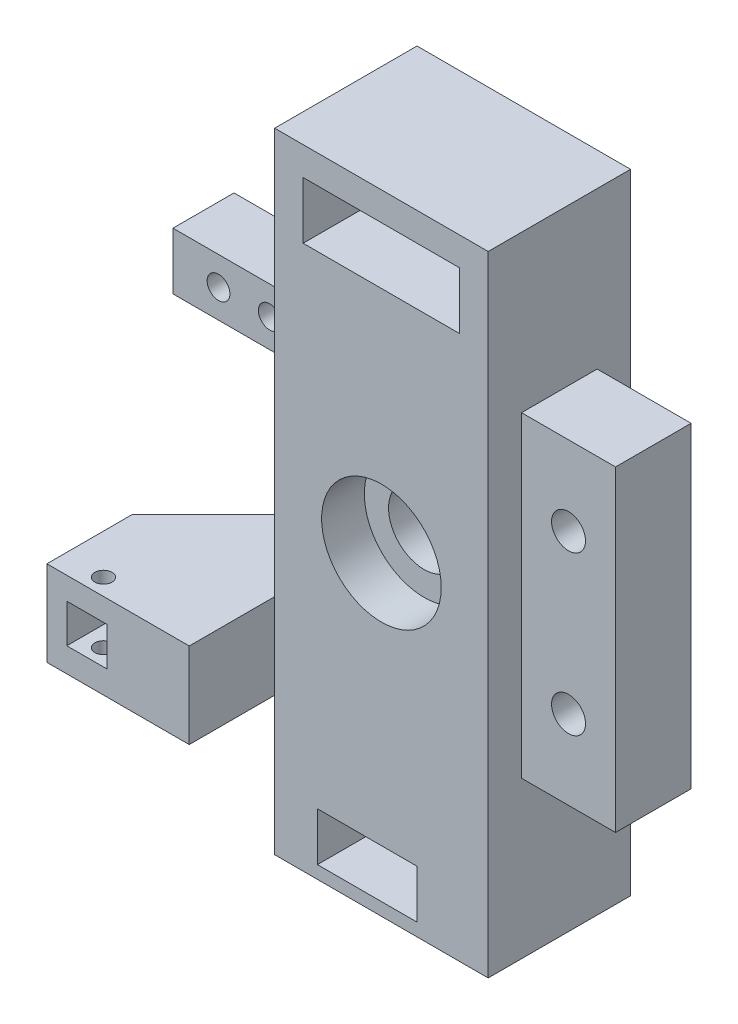
SolidWorks part; units mm, degrees
ref_plane "Front Plane" through (0, 0, 0) normal (0, 0, 1) x (1, 0, 0)
ref_plane "Top Plane" through (0, 0, 0) normal (0, 1, 0) x (1, 0, 0)
ref_plane "Right Plane" through (0, 0, 0) normal (1, 0, 0) x (0, 0, -1)
sketch "Sketch1" plane through (0, 0, 0) normal (0, 1, 0) x (1, 0, 0)
  line L1 (-37.5, -25) -> (37.5, -25)
  line L2 (-37.5, -25) -> (-37.5, 25)
  line L3 (-37.5, 25) -> (37.5, 25)
  line L4 (37.5, -25) -> (37.5, 25)
  line L5 (-37.5, -25) -> (37.5, 25) construction
  line L6 (-37.5, 25) -> (37.5, -25) construction
  point P0 (0, 0)
  dimension "D1" = 50
  dimension "D2" = 75
extrude "BE - main upright body" add sketch "Sketch1" along normal blind 221 contours L3 L4 L1 L2
sketch "Sketch2" plane through (0, 0, 25) normal (0, 0, 1) x (1, 0, 0)
  line L0 (-37.5, 221) -> (37.5, 0) construction
  line L1 (-37.5, 0) -> (37.5, 221) construction
  circle A0 centre (0, 110.5) radius 21
  point P10 (0, 110.5)
  dimension "D1" = 42
sketch "Sketch3" plane through (0, 0, -25) normal (0, 0, -1) x (-1, 0, 0)
  line L0 (-37.5, 0) -> (37.5, 221) construction
  line L1 (-37.5, 221) -> (37.5, 0) construction
  circle A0 centre (0, 110.5) radius 23.5
  point P10 (0, 110.5)
  dimension "D1" = 47
sketch "Sketch4" plane through (0, 0, 25) normal (0, 0, 1) x (1, 0, 0)
  line L0 (-37.5, 221) -> (37.5, 0) construction
  line L1 (37.5, 221) -> (-37.5, 0) construction
  line L2 (-37.5, 0) -> (37.5, 0) construction
  circle A0 centre (0, 110.5) radius 12.5
  dimension "D1" = 25
extrude "CE - Through hole" cut sketch "Sketch4" against normal through all
extrude "CE - Inner bearing" cut sketch "Sketch2" against normal blind 15 contours A0
extrude "CE - Outer bearing" cut sketch "Sketch3" against normal blind 15 contours A0
sketch "Sketch7" plane through (37.5, 0, 0) normal (1, 0, 0) x (0, 0, -1)
  line L0 (25, 221) -> (25, 0) construction
  line L1 (-13.2754, 54.9027) -> (13.2754, 54.9027)
  line L2 (-13.2754, 54.9027) -> (-13.2754, 166.0973)
  line L3 (-13.2754, 166.0973) -> (13.2754, 166.0973)
  line L4 (13.2754, 54.9027) -> (13.2754, 166.0973)
  line L5 (-13.2754, 54.9027) -> (13.2754, 166.0973) construction
  line L6 (-13.2754, 166.0973) -> (13.2754, 54.9027) construction
  line L7 (-25, 110.5) -> (25, 110.5) construction
  line L8 (-25, 221) -> (-25, 0) construction
  point P0 (0, 110.5)
  point P12 (0, 110.5)
extrude "BE - caliper mount" add sketch "Sketch7" along normal blind 33
sketch "Sketch8" plane through (-37.5, 0, 0) normal (-1, 0, 0) x (0, 0, 1)
  line L0 (0, 221) -> (0, 148.4522) construction
  line L1 (-10.7205, 138.4522) -> (10.7205, 138.4522)
  line L2 (-10.7205, 138.4522) -> (-10.7205, 158.4522)
  line L3 (-10.7205, 158.4522) -> (10.7205, 158.4522)
  line L4 (10.7205, 138.4522) -> (10.7205, 158.4522)
  line L5 (-10.7205, 138.4522) -> (10.7205, 158.4522) construction
  line L6 (-10.7205, 158.4522) -> (10.7205, 138.4522) construction
  line L7 (25, 221) -> (-25, 221) construction
  point P0 (0, 148.4522)
  dimension "D1" = 20
extrude "BE - temp sensor mount" add sketch "Sketch8" along normal blind 50
sketch "Sketch9" plane through (-37.5, 0, 0) normal (-1, 0, 0) x (0, 0, 1)
  line L0 (25, 89.5) -> (25, 131.5) construction
  line L1 (-5, 48.5) -> (55, 48.5)
  line L2 (-5, 48.5) -> (-5, 78.5)
  line L3 (-5, 78.5) -> (55, 78.5)
  line L4 (55, 48.5) -> (55, 78.5)
  line L5 (-5, 48.5) -> (55, 78.5) construction
  line L6 (-5, 78.5) -> (55, 48.5) construction
  line L7 (25, 89.5) -> (25, 131.5) construction
  line L8 (25, 221) -> (25, 0) construction
  point P0 (25, 63.5)
  point P7 (25, 110.5)
  dimension "D1" = 47
  dimension "D2" = 60
  dimension "D3" = 30
extrude "BE - tie rod mount" add sketch "Sketch9" along normal blind 50
sketch "Sketch10" plane through (0, 0, 13.2754) normal (0, 0, 1) x (1, 0, 0)
  line L0 (54, 166.0973) -> (54, 54.9027) construction
  line L1 (70.5, 166.0973) -> (37.5, 166.0973) construction
  line L2 (70.5, 54.9027) -> (37.5, 54.9027) construction
  line L3 (37.5, 166.0973) -> (70.5, 110.5) construction
  line L4 (70.5, 166.0973) -> (70.5, 54.9027) construction
  line L5 (70.5, 166.0973) -> (37.5, 110.5) construction
  line L6 (37.5, 166.0973) -> (37.5, 54.9027) construction
  line L7 (37.5, 110.5) -> (70.5, 54.9027) construction
  line L8 (37.5, 54.9027) -> (70.5, 110.5) construction
  circle A0 centre (54, 138.2986) radius 5.968
  circle A1 centre (54, 82.7014) radius 5.968
  point P20 (54, 138.2986)
extrude "CE - caliper holes" cut sketch "Sketch10" against normal through all
sketch "Sketch12" plane through (0, 0, 25) normal (0, 0, 1) x (1, 0, 0)
  line L0 (-12.5, 201) -> (12.5, 201) construction
  line L2 (-37.5, 221) -> (37.5, 221) construction
  circle A0 centre (-12.5, 201) radius 4
  circle A1 centre (12.5, 201) radius 4
  point P2 (0, 201)
  dimension "D1" = 8
  dimension "D2" = 20
  dimension "D3" = 25
extrude "CE - top clevis holes" cut sketch "Sketch12" against normal through all
sketch "Sketch13" plane through (0, 0, 25) normal (0, 0, 1) x (1, 0, 0)
  line L0 (-37.5, 221) -> (37.5, 221) construction
  line L1 (-27.5, 191) -> (27.5, 191)
  line L2 (-27.5, 191) -> (-27.5, 211)
  line L3 (-27.5, 211) -> (27.5, 211)
  line L4 (27.5, 191) -> (27.5, 211)
  line L5 (-27.5, 191) -> (27.5, 211) construction
  line L6 (-27.5, 211) -> (27.5, 191) construction
  point P0 (0, 201)
  dimension "D1" = 20
  dimension "D2" = 55
  dimension "D3" = 20
extrude "CE - top clevis space" cut sketch "Sketch13" against normal blind 35 contours L3 L4 L1 L2
ref_plane "Top clevis plane" through (0, 0, 5) normal (0, 0, 1) x (1, 0, 0)
ref_point "Position of Top Clevis"
sketch "Sketch14" plane through (0, 0, 25) normal (0, 0, 1) x (1, 0, 0)
  line L1 (-22.48, 4.5) -> (2.52, 4.5)
  line L2 (-22.48, 4.5) -> (-22.48, 16.5)
  line L3 (-22.48, 16.5) -> (2.52, 16.5)
  line L4 (2.52, 4.5) -> (2.52, 16.5)
  line L5 (-22.48, 4.5) -> (2.52, 16.5) construction
  line L6 (-22.48, 16.5) -> (2.52, 4.5) construction
  point P0 (-9.98, 10.5)
  dimension "D1" = 9.98
  dimension "D2" = 190.5
  dimension "D3" = 12
  dimension "D4" = 25
extrude "CE - bottom clevis space" cut sketch "Sketch14" against normal through all
ref_plane "Bottom Clevis Plane" through (0, 0, -1.65) normal (0, 0, 1) x (1, 0, 0)
ref_point "Position of Bottom Clevis"
sketch "Sketch15" plane through (0, 0, 25) normal (0, 0, 1) x (1, 0, 0)
  line L0 (2.52, 4.5) -> (2.52, 16.5) construction
  line L1 (-22.48, 16.5) -> (2.52, 16.5)
  line L2 (-22.48, 16.5) -> (-22.48, 21.5)
  line L3 (-22.48, 21.5) -> (2.52, 21.5)
  line L4 (2.52, 16.5) -> (2.52, 21.5)
  dimension "D1" = 5
extrude "CE - expand bottom clevis" cut sketch "Sketch15" against normal through all
ref_plane "P - front of part" through (2.52, 4.5, 25) normal (0, 0, 1) x (1, 0, 0)
sketch "Sketch16" plane through (2.52, 4.5, 25) normal (0, 0, 1) x (1, 0, 0)
  line L0 (0, 17) -> (-25, 17) construction
  line L1 (0, 0) -> (10.0076, 0)
  line L2 (0, 0) -> (0, 17)
  line L3 (0, 17) -> (10.0076, 17)
  line L4 (10.0076, 0) -> (10.0076, 17)
  dimension "D1" = 10.0076
extrude "CE - widen bottom clevis" cut sketch "Sketch16" against normal through all and the other way through all
chamfer "Chamfer1" distance 30 angle 45 1 edges at (-87.5, 63.5, -5)
ref_plane "P - xy plane containing bottom clevis" through (0, 10.5, 0) normal (0, 1, 0) x (1, 0, 0)
ref_plane "P - xy plane containing tie rod" through (0, 63.84, 0) normal (0, 1, 0) x (1, 0, 0)
sketch "Sketch17" plane through (0, 63.84, 0) normal (0, 1, 0) x (1, 0, 0)
  point P0 (-73.48, -49.15)
  point P1 (-9.98, 1.65)
  point P3 (-9.98, 1.65)
  dimension "D1" = 63.5
  dimension "D2" = 50.8
ref_point "Position of Tie Rod"
sketch "Sketch18" plane through (0, 0, 55) normal (0, 0, 1) x (1, 0, 0)
  line L1 (-80.502, 57.0586) -> (-66.458, 57.0586)
  line L2 (-80.502, 57.0586) -> (-80.502, 70.6214)
  line L3 (-80.502, 70.6214) -> (-66.458, 70.6214)
  line L4 (-66.458, 57.0586) -> (-66.458, 70.6214)
  line L5 (-80.502, 57.0586) -> (-66.458, 70.6214) construction
  line L6 (-80.502, 70.6214) -> (-66.458, 57.0586) construction
  point P0 (-73.48, 63.84)
  point P2 (-73.48, 63.84)
extrude "Cut-Extrude1" cut sketch "Sketch18" against normal blind 20
sketch "Sketch19" plane through (0, 78.5, 0) normal (0, 1, 0) x (1, 0, 0)
  circle A0 centre (-73.48, -49.15) radius 3
  point P2 (-73.48, -49.15)
  dimension "D1" = 6
extrude "Cut-Extrude2" cut sketch "Sketch19" against normal through all
sketch "Sketch20" plane through (0, 0, 10.7205) normal (0, 0, 1) x (1, 0, 0)
  line L0 (-87.5, 148.4522) -> (-37.5, 148.4522) construction
  line L1 (-87.5, 138.4522) -> (-87.5, 158.4522) construction
  line L2 (-37.5, 138.4522) -> (-37.5, 158.4522) construction
  line L3 (-87.5, 158.4522) -> (-87.5, 138.4522) construction
  line L4 (-53.5026, 148.4522) -> (-71.4974, 148.4522) construction
  circle A0 centre (-53.5026, 148.4522) radius 4
  circle A1 centre (-71.4974, 148.4522) radius 4
  point P10 (-62.5, 148.4522)
  point P13 (-44.3585, 148.4522)
  point P16 (-53.5026, 148.4522)
  point P18 (-61.91, 148.335)
  dimension "D1" = 8
extrude "Cut-Extrude3" cut sketch "Sketch20" against normal through all contours A0 | A1
equation "\"clevis_pin_y\"=20"
equation "\"D2@Sketch12\"=\"clevis_pin_y\""
equation "\"clevis_pin_dist\"=25"
equation "\"D3@Sketch12\"=\"clevis_pin_dist\""
equation "\"D2@Sketch13\"=\"clevis_pin_dist\" + 30"
equation "\"D1@Sketch13\"=\"clevis_pin_y\""
equation "\"x_dist_a_arms\"=9.98"
equation "\"D1@Sketch14\"=\"x_dist_a_arms\""
equation "\"y_dist_a_arms\"=190.5"
equation "\"D2@Sketch14\"=\"y_dist_a_arms\""
equation "\"y_dist_bottom_clevis_to_tie_rod\"= 53.34"
equation "\"x_dist_bottom_clevis_to_tie_rod\"= 63.50"
equation "\"z_dist_bottom_clevis_to_tie_rod\"= 50.80"
